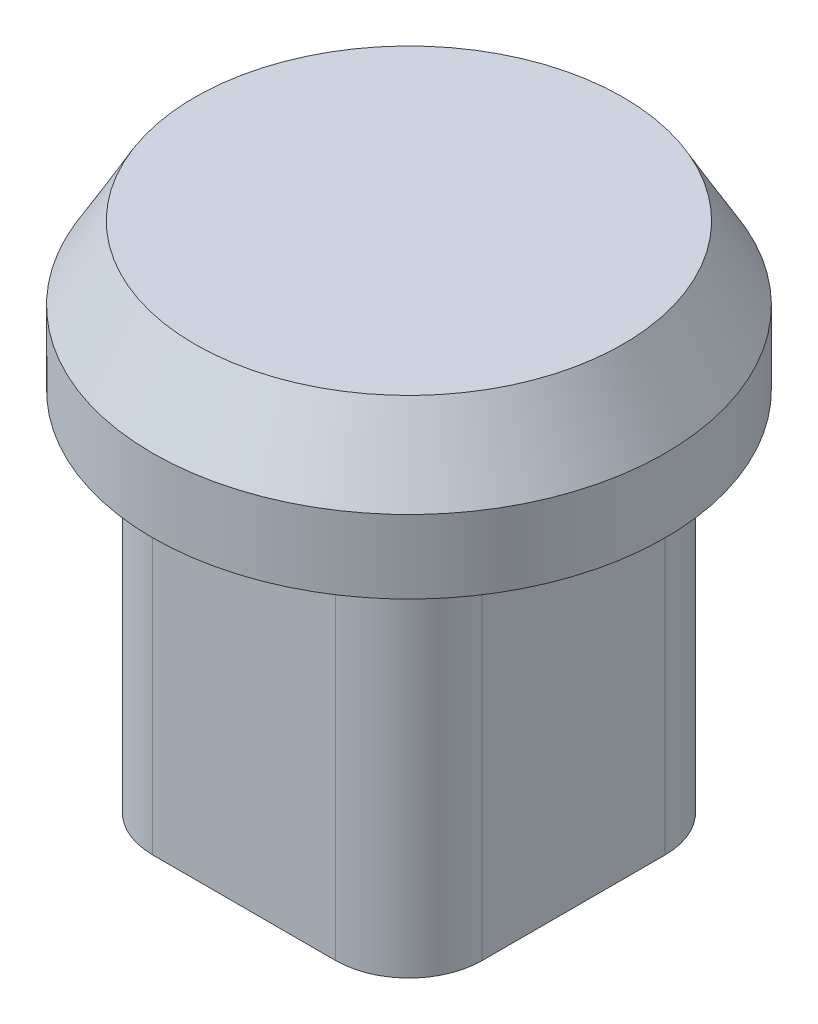
SolidWorks part; units mm, degrees
ref_plane "Спереди" through (0, 0, 0) normal (0, 0, 1) x (1, 0, 0)
ref_plane "Сверху" through (0, 0, 0) normal (0, 1, 0) x (1, 0, 0)
ref_plane "Справа" through (0, 0, 0) normal (1, 0, 0) x (0, 0, -1)
sketch "Эскиз2" plane through (0, 0, 0) normal (0, 1, 0) x (1, 0, 0)
  line L1 (-2.25, -2.25) -> (2.25, -2.25)
  line L2 (-2.25, -2.25) -> (-2.25, 2.25)
  line L3 (-2.25, 2.25) -> (2.25, 2.25)
  line L4 (2.25, -2.25) -> (2.25, 2.25)
  line L5 (-2.25, -2.25) -> (2.25, 2.25) construction
  line L6 (-2.25, 2.25) -> (2.25, -2.25) construction
  point P0 (0, 0)
  dimension "D1" = 4.5
extrude "Бобышка-Вытянуть1" add sketch "Эскиз2" along normal blind 5
sketch "Эскиз3" plane through (0, 5, 0) normal (0, 1, 0) x (1, 0, 0)
  circle A0 centre (0, 0) radius 3.5
  dimension "D1" = 7
extrude "Бобышка-Вытянуть2" add sketch "Эскиз3" along normal blind 2
chamfer "Фаска1" distance 1 angle 30 1 edges at (0, 7, 3.5)
fillet "Скругление1" radius 1 4 edges at (2.25, 2.5, -2.25) (2.25, 2.5, 2.25) (-2.25, 2.5, -2.25) (-2.25, 2.5, 2.25)
